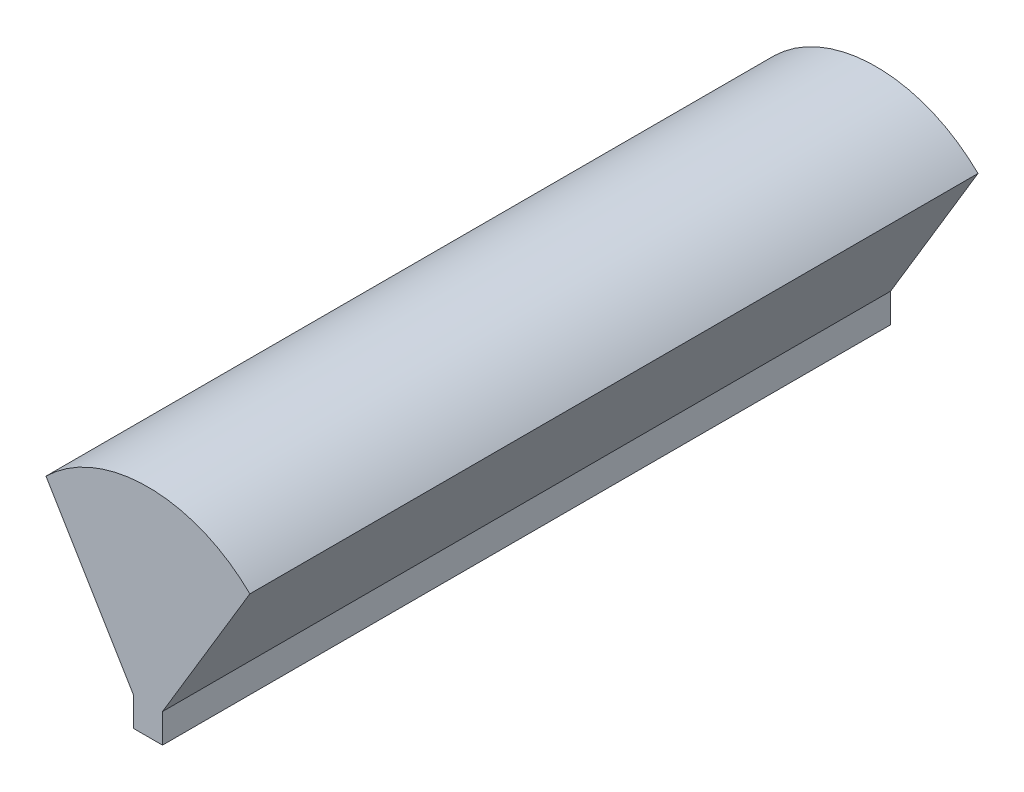
SolidWorks part; units mm, degrees
ref_plane "Front Plane" through (0, 0, 0) normal (0, 0, 1) x (1, 0, 0)
ref_plane "Top Plane" through (0, 0, 0) normal (0, 1, 0) x (1, 0, 0)
ref_plane "Right Plane" through (0, 0, 0) normal (1, 0, 0) x (0, 0, -1)
sketch "Sketch1" plane through (0, 0, 0) normal (0, 0, 1) x (1, 0, 0)
  line L0 (0, 0) -> (2, 0)
  line L1 (2, 0) -> (2, 2)
  line L2 (2, 2) -> (8, 12)
  line L3 (8, 12) -> (-6, 12)
  line L4 (-6, 12) -> (0, 2)
  line L5 (0, 2) -> (0, 0)
  dimension "D1" = 2
  dimension "D2" = 2
  dimension "D3" = 14
  dimension "D4" = 12
  dimension "D5" = 6
  dimension "D6" = 2
extrude "Boss-Extrude1" add sketch "Sketch1" along normal blind 50
sketch "Sketch2" plane through (0, 0, 50) normal (0, 0, 1) x (1, 0, 0)
  line L0 (-6, 12) -> (8, 12)
  arc A0 (-6, 12) -> (8, 12) centre (1, 4.8586) cw
  dimension "D1" = 10
extrude "Boss-Extrude2" add sketch "Sketch2" against normal blind 50
